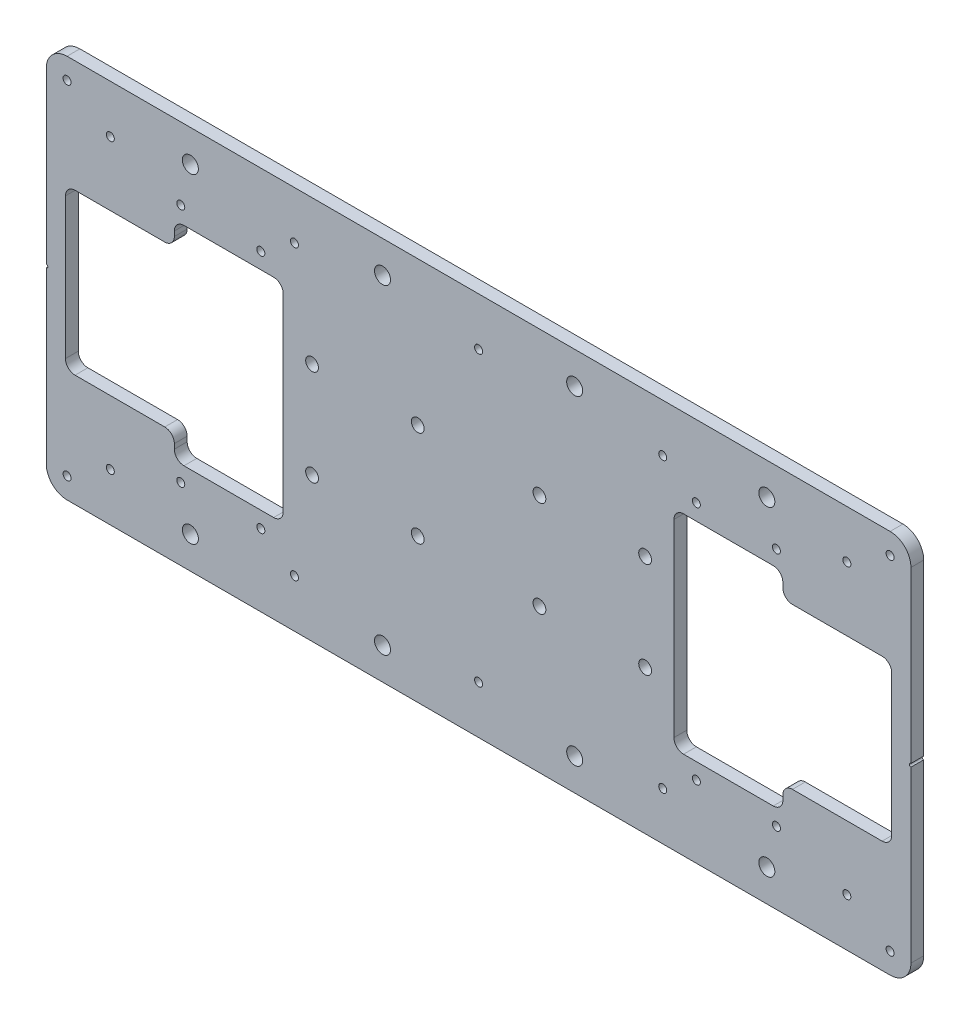
SolidWorks part; units mm, degrees
ref_plane "Plan de face" through (0, 0, 0) normal (0, 0, 1) x (1, 0, 0)
ref_plane "Plan de dessus" through (0, 0, 0) normal (0, 1, 0) x (1, 0, 0)
ref_plane "Plan de droite" through (0, 0, 0) normal (1, 0, 0) x (0, 0, -1)
sketch "Esquisse1" plane through (0, 0, 0) normal (0, 0, 1) x (1, 0, 0)
  line L1 (0, 60) -> (135, 60)
  line L2 (0, 60) -> (0, -60)
  line L3 (0, -60) -> (135, -60)
  line L4 (135, 60) -> (135, -60)
  line L5 (0, 60) -> (135, -60) construction
  line L6 (0, -60) -> (135, 60) construction
  point P0 (67.5, 0)
  dimension "D1" = 135
  dimension "D2" = 120
extrude "Boss.-Extru.1" add sketch "Esquisse1" along normal blind 4
sketch "Esquisse2" plane through (0, 0, 4) normal (0, 0, 1) x (1, 0, 0)
  line L0 (95, -25) -> (95, -32.5)
  line L5 (95, 25) -> (129, 25)
  line L11 (95, -25) -> (129, -25)
  line L12 (129, 25) -> (129, -25)
  line L13 (95, 32.5) -> (61, 32.5)
  line L14 (95, 32.5) -> (95, 25)
  line L15 (95, -32.5) -> (61, -32.5)
  line L16 (61, 32.5) -> (61, -32.5)
  line L21 (135, -60) -> (135, 60) construction
  dimension "D1" = 34
  dimension "D2" = 34
  dimension "D3" = 50
  dimension "D4" = 65
  dimension "D5" = 6
extrude "Enlèv. mat.-Extru.1" cut sketch "Esquisse2" against normal up to next
fillet "Congé1" radius 3 8 edges at (129, -25, 2) (95, -32.5, 2) (61, -32.5, 2) (95, -25, 2) (95, 25, 2) (129, 25, 2) (95, 32.5, 2) (61, 32.5, 2)
sketch "Esquisse3" plane through (0, 0, 4) normal (0, 0, 1) x (1, 0, 0)
  line L0 (135, 60) -> (0, 60) construction
  line L1 (30, 50) -> (90, 50) construction
  line L2 (30, 50) -> (30, -50) construction
  line L3 (30, -50) -> (90, -50) construction
  line L4 (90, 50) -> (90, -50) construction
  line L5 (135, -60) -> (135, 60) construction
  line L6 (128.5, 53.5) -> (128.5, -53.5) construction
  line L7 (115, 45) -> (0, 45) construction
  line L8 (115, 45) -> (115, -45) construction
  line L9 (115, -45) -> (0, -45) construction
  line L10 (0, 45) -> (0, -45) construction
  line L11 (135, -60) -> (135, 60) construction
  line L12 (52, 15) -> (19, 15) construction
  line L13 (52, 15) -> (52, -15) construction
  line L14 (52, -15) -> (19, -15) construction
  line L15 (19, 15) -> (19, -15) construction
  circle A0 centre (30, 50) radius 2.5
  circle A1 centre (90, 50) radius 2.5
  circle A2 centre (90, -50) radius 2.5
  circle A3 centre (30, -50) radius 2.5
  circle A4 centre (0, 45) radius 1.25
  circle A5 centre (115, 45) radius 1.25
  circle A6 centre (115, -45) radius 1.25
  circle A7 centre (0, -45) radius 1.25
  circle A8 centre (57.5, -45) radius 1.25
  circle A9 centre (57.5, 45) radius 1.25
  circle A10 centre (128.5, 53.5) radius 1.25
  circle A11 centre (128.5, -53.5) radius 1.25
  circle A12 centre (135, 0) radius 0.5
  circle A13 centre (52, 15) radius 2
  circle A14 centre (19, 15) radius 2
  circle A15 centre (19, -15) radius 2
  circle A16 centre (52, -15) radius 2
  point P11 (30, 0)
  point P30 (128.5, 0)
  point P41 (19, 0)
  dimension "D1" = 5
  dimension "D5" = 2.5
  dimension "D10" = 2.5
  dimension "D11" = 1
  dimension "D15" = 4
  dimension "D2" = 10
  dimension "D3" = 45
  dimension "D4" = 60
  dimension "D6" = 15
  dimension "D7" = 20
  dimension "D8" = 6.5
  dimension "D9" = 6.5
  dimension "D12" = 83
  dimension "D13" = 33
  dimension "D14" = 30
extrude "Enlèv. mat.-Extru.2" cut sketch "Esquisse3" against normal up to next
sketch "Esquisse4" plane through (0, 0, 4) normal (0, 0, 1) x (1, 0, 0)
  line L0 (135, 60) -> (0, 60) construction
  line L1 (68, 37.5) -> (93, 37.5) construction
  line L2 (68, 37.5) -> (68, -37.5) construction
  line L3 (68, -37.5) -> (93, -37.5) construction
  line L4 (93, 37.5) -> (93, -37.5) construction
  line L5 (135, 0.5) -> (135, 60) construction
  circle A0 centre (68, 37.5) radius 1.25
  circle A1 centre (93, 37.5) radius 1.25
  circle A2 centre (68, -37.5) radius 1.25
  circle A3 centre (93, -37.5) radius 1.25
  point P13 (68, 0)
  dimension "D1" = 2.5
  dimension "D2" = 22.5
  dimension "D3" = 42
  dimension "D4" = 25
extrude "Enlèv. mat.-Extru.3" cut sketch "Esquisse4" against normal up to next
fillet "Congé2" radius 6.5 2 edges at (135, 60, 2) (135, -60, 2)
mirror "Symétrie1" about plane through (0, 60, 4) normal (1, 0, 0) of bodies 105 103
